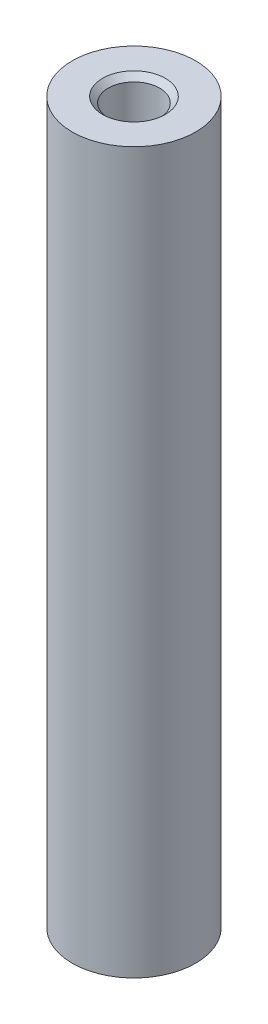
SolidWorks part; units mm, degrees
material "6061 合金"
ref_plane "前视基准面" through (0, 0, 0) normal (0, 0, 1) x (1, 0, 0)
ref_plane "上视基准面" through (0, 0, 0) normal (0, 1, 0) x (1, 0, 0)
ref_plane "右视基准面" through (0, 0, 0) normal (1, 0, 0) x (0, 0, -1)
sketch "草图1" plane through (0, 0, 0) normal (0, 1, 0) x (1, 0, 0)
  circle A0 centre (0, 0) radius 3
  dimension "D1" = 6
extrude "凸台-拉伸1" add sketch "草图1" along normal blind 35
hole_wizard "M3 螺纹孔1" positions "草图2" profile "草图3" tap size "M3" standard "GB" end condition through all
sketch "草图2" plane through (0, 35, 0) normal (0, 1, 0) x (1, 0, 0)
  point P0 (0, 0)
sketch "草图3" plane through (0, 35, 0) normal (1, 0, 0) x (0, 0, 1)
  line L0 (0, 0) -> (0, 35)
  line L1 (0, 35) -> (1.25, 35)
  line L2 (1.25, 35) -> (1.25, 0.275)
  line L3 (1.25, 0.275) -> (1.525, 0)
  line L5 (1.525, 0) -> (0, 0)
  line L6 (-1.25, 0.275) -> (-1.525, 0) construction
  line L11 (0, -6.35) -> (0, 107.95) construction
  dimension "通孔螺纹孔钻头直径" = 2.5
  dimension "通孔螺纹孔钻头深度" = 35
  dimension "近端锥形沉头孔直径" = 3.05
  dimension "近端锥形沉头孔角度" = 90
cosmetic thread "孔螺蚊线1"
